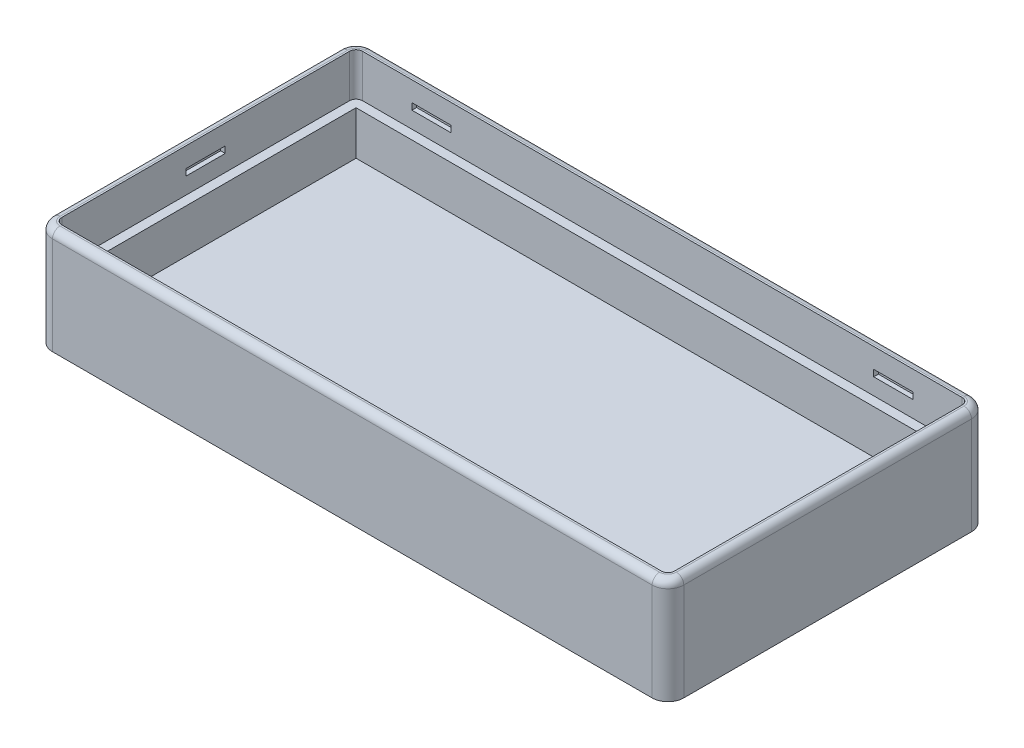
SolidWorks part; units mm, degrees
ref_plane "前视基准面" through (0, 0, 0) normal (0, 0, 1) x (1, 0, 0)
ref_plane "上视基准面" through (0, 0, 0) normal (0, 1, 0) x (1, 0, 0)
ref_plane "右视基准面" through (0, 0, 0) normal (1, 0, 0) x (0, 0, -1)
other "Configuration Table"
sketch "草图1" plane through (0, 0, 0) normal (0, 1, 0) x (1, 0, 0)
  line L1 (-32.2, 17.15) -> (32.2, 17.15)
  line L2 (-33.9, 15.45) -> (-33.9, -15.45)
  line L3 (-32.2, -17.15) -> (32.2, -17.15)
  line L4 (33.9, 15.45) -> (33.9, -15.45)
  line L5 (-33.9, 17.15) -> (33.9, -17.15) construction
  line L6 (-33.9, -17.15) -> (33.9, 17.15) construction
  arc A0 (32.2, 17.15) -> (33.9, 15.45) centre (32.2, 15.45) cw
  arc A1 (32.2, -17.15) -> (33.9, -15.45) centre (32.2, -15.45) ccw
  arc A2 (-33.9, -15.45) -> (-32.2, -17.15) centre (-32.2, -15.45) ccw
  arc A3 (-32.2, 17.15) -> (-33.9, 15.45) centre (-32.2, 15.45) ccw
  point P0 (0, 0)
  dimension "D3" = 1.7
  dimension "D1" = 67.8
  dimension "D2" = 34.3
extrude "凸台-拉伸1" add sketch "草图1" along normal blind 11.3
sketch "草图2" plane through (0, 11.3, 0) normal (0, 1, 0) x (1, 0, 0)
  line L8 (32.9, -15.45) -> (32.9, 15.45)
  line L9 (-32.2, -16.15) -> (32.2, -16.15)
  line L10 (-32.9, 15.45) -> (-32.9, -15.45)
  line L11 (32.2, 16.15) -> (-32.2, 16.15)
  line L12 (32.9, -15.45) -> (32.9, 15.45)
  line L13 (-32.2, -16.15) -> (32.2, -16.15)
  line L14 (-32.9, 15.45) -> (-32.9, -15.45)
  line L15 (32.2, 16.15) -> (-32.2, 16.15)
  arc A8 (32.9, 15.45) -> (32.2, 16.15) centre (32.2, 15.45) ccw
  arc A9 (32.2, -16.15) -> (32.9, -15.45) centre (32.2, -15.45) ccw
  arc A10 (-32.9, -15.45) -> (-32.2, -16.15) centre (-32.2, -15.45) ccw
  arc A11 (-32.2, 16.15) -> (-32.9, 15.45) centre (-32.2, 15.45) ccw
  arc A12 (32.9, 15.45) -> (32.2, 16.15) centre (32.2, 15.45) ccw
  arc A13 (32.2, -16.15) -> (32.9, -15.45) centre (32.2, -15.45) ccw
  arc A14 (-32.9, -15.45) -> (-32.2, -16.15) centre (-32.2, -15.45) ccw
  arc A15 (-32.2, 16.15) -> (-32.9, 15.45) centre (-32.2, 15.45) ccw
  dimension "D1" = 1
extrude "切除-拉伸1" cut sketch "草图2" against normal blind 4.6
sketch "草图3" plane through (0, 6.7, 0) normal (0, 1, 0) x (1, 0, 0)
  line L25 (31.9, -15.15) -> (31.9, 15.15)
  line L26 (-31.9, -15.15) -> (31.9, -15.15)
  line L27 (-31.9, 15.15) -> (-31.9, -15.15)
  line L28 (31.9, 15.15) -> (-31.9, 15.15)
  line L29 (31.9, -15.15) -> (31.9, 15.15)
  line L30 (-31.9, -15.15) -> (31.9, -15.15)
  line L31 (-31.9, 15.15) -> (-31.9, -15.15)
  line L32 (31.9, 15.15) -> (-31.9, 15.15)
  dimension "D1" = 1
extrude "切除-拉伸2" cut sketch "草图3" against normal offset from surface (4.7 mm away) 2 up to face at (0, 0, 0)
sketch "草图4" plane through (-32.9, 0, 0) normal (1, 0, 0) x (0, 0, -1)
  line L1 (-2.1, 9.17) -> (2.1, 9.17)
  line L2 (-2.1, 9.17) -> (-2.1, 8.47)
  line L3 (-2.1, 8.47) -> (2.1, 8.47)
  line L4 (2.1, 9.17) -> (2.1, 8.47)
  line L5 (-16.15, 6.7) -> (-16.15, 11.3) construction
  line L6 (15.45, 6.7) -> (-15.45, 6.7) construction
  dimension "D1" = 4.2
  dimension "D2" = 0.7
  dimension "D3" = 14.05
  dimension "D4" = 1.77
extrude "切除-拉伸3" cut sketch "草图4" against normal blind 0.5
ref_plane "基准面1" through (0, 0, 0) normal (1, 0, 0) x (0, 0, -1)
mirror "镜向1" about plane through (0, 0, 0) normal (1, 0, 0) of "切除-拉伸3"
sketch "草图5" plane through (0, 0, 16.15) normal (0, 0, -1) x (-1, 0, 0)
  line L1 (-26.9, 9.17) -> (-22.7, 9.17)
  line L2 (-26.9, 9.17) -> (-26.9, 8.47)
  line L3 (-26.9, 8.47) -> (-22.7, 8.47)
  line L4 (-22.7, 9.17) -> (-22.7, 8.47)
  line L5 (-32.9, 6.7) -> (-32.9, 11.3) construction
  line L6 (32.2, 6.7) -> (-32.2, 6.7) construction
  line L7 (0, 55) -> (0, -55) construction
  line L8 (26.9, 8.47) -> (22.7, 8.47)
  line L9 (22.7, 9.17) -> (22.7, 8.47)
  line L10 (26.9, 9.17) -> (22.7, 9.17)
  line L11 (26.9, 9.17) -> (26.9, 8.47)
  dimension "D1" = 4.2
  dimension "D2" = 0.7
  dimension "D3" = 10.2
  dimension "D4" = 1.77
extrude "切除-拉伸4" cut sketch "草图5" against normal blind 0.5
mirror "镜向2" about plane through (0, 0, 0) normal (0, 0, 1) of "切除-拉伸4"
fillet "圆角4" radius 0.8 8 edges at (33.4021, 11.3, -16.6521) (0, 11.3, -17.15) (-33.4021, 11.3, -16.6521) (-33.9, 11.3, 0) (-33.4021, 11.3, 16.6521) (0, 11.3, 17.15) (33.4021, 11.3, 16.6521) (33.9, 11.3, 0)
